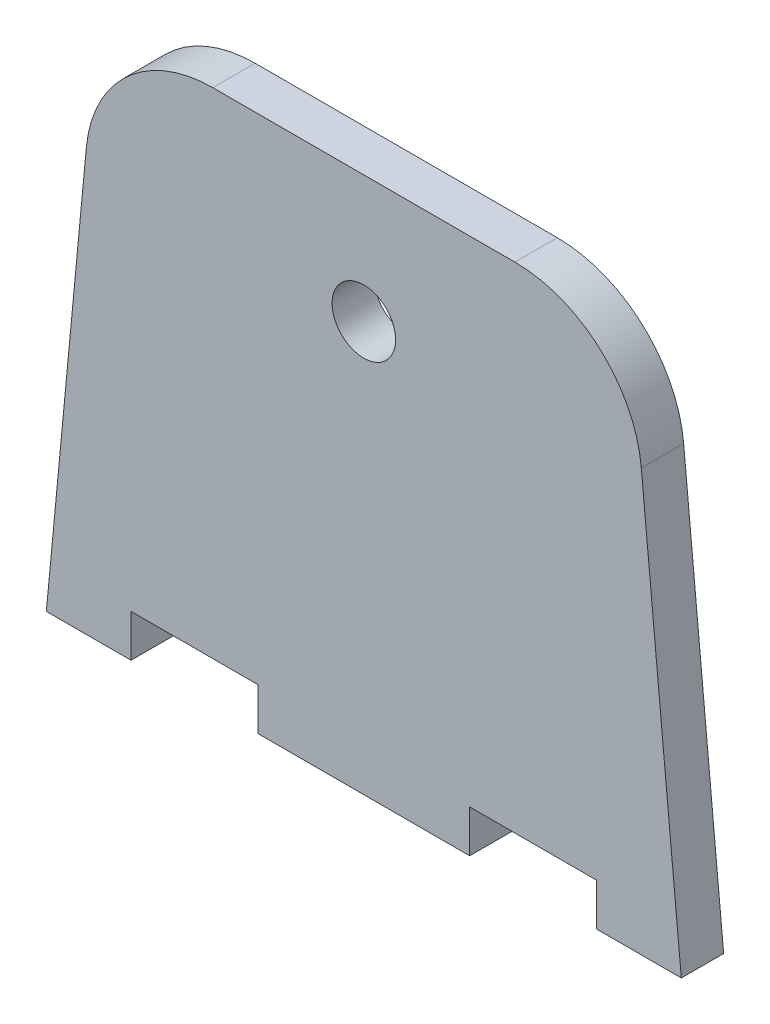
SolidWorks part; units mm, degrees
ref_plane "Front Plane" through (0, 0, 0) normal (0, 0, 1) x (1, 0, 0)
ref_plane "Top Plane" through (0, 0, 0) normal (0, 1, 0) x (1, 0, 0)
ref_plane "Right Plane" through (0, 0, 0) normal (1, 0, 0) x (0, 0, -1)
sketch "Sketch1" plane through (0, 0, 0) normal (0, 0, 1) x (1, 0, 0)
  line L0 (-23.8125, 0) -> (23.8125, 0)
  line L1 (-23.8125, 0) -> (-20.8128, 31.6332)
  line L2 (23.8125, 0) -> (20.8128, 31.6332)
  line L3 (6.35, 184.15) -> (-6.35, 184.15)
  line L4 (-11.3303, 40.259) -> (11.3303, 40.259)
  circle A0 centre (0, 30.734) radius 2.3812
  arc A1 (11.3303, 40.259) -> (20.8128, 31.6332) centre (11.3303, 30.734) cw
  arc A2 (-11.3303, 40.259) -> (-20.8128, 31.6332) centre (-11.3303, 30.734) ccw
  dimension "D1" = 4.7625
  dimension "D2" = 30.734
  dimension "D3" = 12.7
  dimension "D8" = 9.525
  dimension "D4" = 47.625
  dimension "D5" = 23.8125
  dimension "D6" = 9.525
  dimension "D7" = 184.15
extrude "Boss-Extrude1" add sketch "Sketch1" along normal blind 3.175 contours L4 A2 L1 L0 L2 A1 A0
sketch "Sketch2" plane through (0, 0, 3.175) normal (0, 0, 1) x (1, 0, 0)
  line L0 (-23.8125, 0) -> (23.8125, 0) construction
  line L1 (-17.4625, 0) -> (-7.9375, 0)
  line L2 (-17.4625, 0) -> (-17.4625, 3.175)
  line L3 (-17.4625, 3.175) -> (-7.9375, 3.175)
  line L4 (-7.9375, 0) -> (-7.9375, 3.175)
  line L6 (17.4625, 0) -> (7.9375, 0)
  line L7 (17.4625, 0) -> (17.4625, 3.175)
  line L8 (17.4625, 3.175) -> (7.9375, 3.175)
  line L9 (7.9375, 0) -> (7.9375, 3.175)
  dimension "D1" = 3.175
  dimension "D2" = 9.525
  dimension "D3" = 9.525
  dimension "D4" = 3.175
  dimension "D5" = 6.35
  dimension "D6" = 6.35
extrude "Cut-Extrude1" cut sketch "Sketch2" against normal through all
